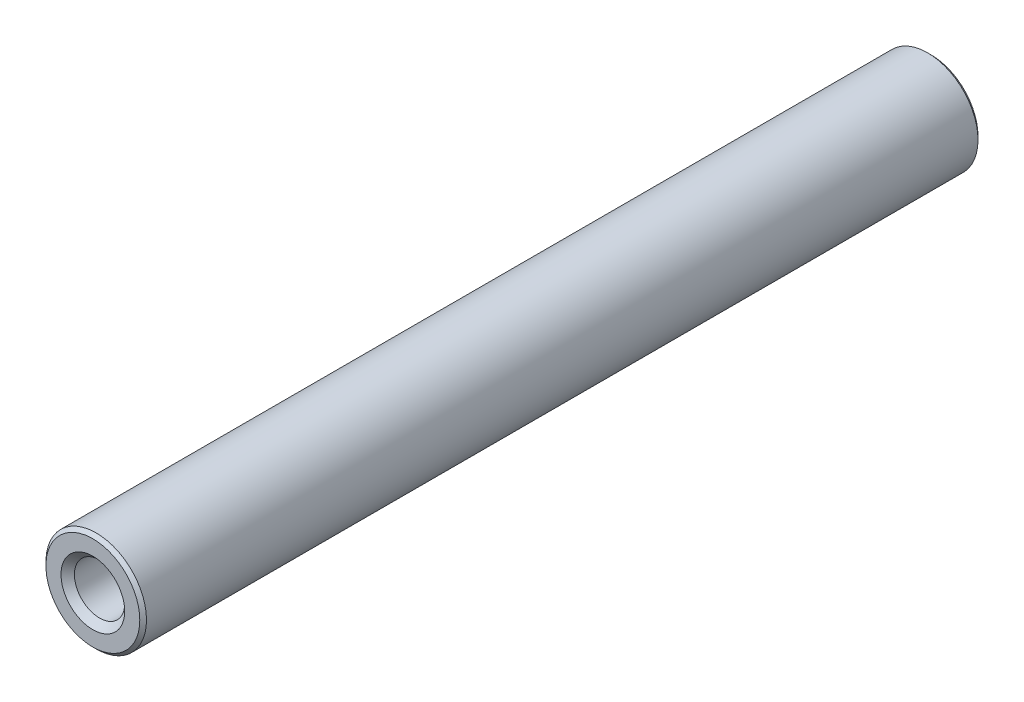
SolidWorks part; units mm, degrees
ref_plane "前视基准面" through (0, 0, 0) normal (0, 0, 1) x (1, 0, 0)
ref_plane "上视基准面" through (0, 0, 0) normal (0, 1, 0) x (1, 0, 0)
ref_plane "右视基准面" through (0, 0, 0) normal (1, 0, 0) x (0, 0, -1)
sketch "草图1" plane through (0, 0, 0) normal (0, 1, 0) x (1, 0, 0)
  line L0 (1.5, 17) -> (0, 17)
  line L1 (0, 17) -> (0, -17)
  line L2 (0, -17) -> (1.5, -17)
  line L3 (1.5, -17) -> (1.5, -24.6001)
  line L4 (1.5, -24.6001) -> (1.8999, -25)
  line L5 (1.8999, -25) -> (2.7999, -25)
  line L6 (2.7999, -25) -> (3, -24.7999)
  line L7 (3, -24.7999) -> (3, 24.8)
  line L8 (3, 24.8) -> (2.8, 25)
  line L9 (2.8, 25) -> (1.8999, 25)
  line L10 (1.8999, 25) -> (1.5, 24.6001)
  line L11 (1.5, 24.6001) -> (1.5, 17)
  line L12 (0, 25.0031) -> (0, -25) construction
revolve "旋转1" add sketch "草图1" angle 360 about L12
